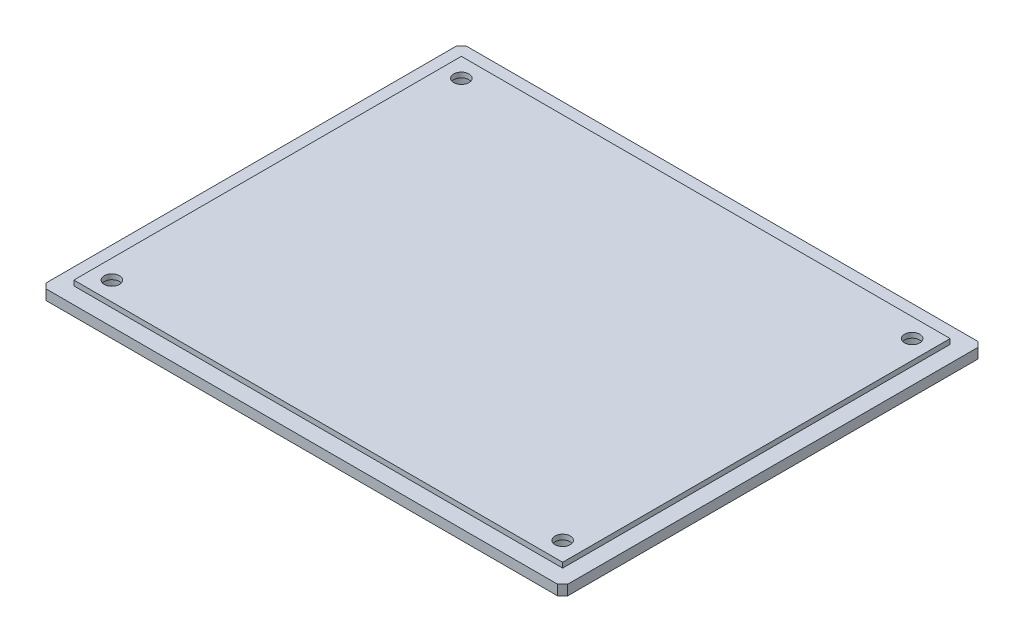
SolidWorks part; units mm, degrees
ref_plane "前视基准面" through (0, 0, 0) normal (0, 0, 1) x (1, 0, 0)
ref_plane "上视基准面" through (0, 0, 0) normal (0, 1, 0) x (1, 0, 0)
ref_plane "右视基准面" through (0, 0, 0) normal (1, 0, 0) x (0, 0, -1)
other "Configuration Table"
sketch "Sketch1" plane through (0, 0, 0) normal (0, 1, 0) x (1, 0, 0)
  line L1 (-51.5, 41.5) -> (51.5, 41.5)
  line L2 (-51.5, 41.5) -> (-51.5, -41.5)
  line L3 (-51.5, -41.5) -> (51.5, -41.5)
  line L4 (51.5, 41.5) -> (51.5, -41.5)
  line L5 (-51.5, 41.5) -> (51.5, -41.5) construction
  line L6 (-51.5, -41.5) -> (51.5, 41.5) construction
  point P0 (0, 0)
  dimension "D1" = 103
  dimension "D2" = 83
extrude "Boss-Extrude1" add sketch "Sketch1" along normal blind 2
sketch "Sketch2" plane through (0, 2, 0) normal (0, 1, 0) x (1, 0, 0)
  line L1 (-48.25, 38.25) -> (48.25, 38.25)
  line L2 (-48.25, 38.25) -> (-48.25, -38.25)
  line L3 (-48.25, -38.25) -> (48.25, -38.25)
  line L4 (48.25, 38.25) -> (48.25, -38.25)
  line L5 (-48.25, 38.25) -> (48.25, -38.25) construction
  line L6 (-48.25, -38.25) -> (48.25, 38.25) construction
  point P0 (0, 0)
  dimension "D1" = 96.5
  dimension "D2" = 76.5
extrude "Boss-Extrude2" add sketch "Sketch2" along normal blind 1
chamfer "Chamfer1" distance 1 angle 45 4 edges at (51.5, 1, -41.5) (51.5, 1, 41.5) (-51.5, 1, 41.5) (-51.5, 1, -41.5)
sketch "Sketch3" plane through (0, 3, 0) normal (0, 1, 0) x (1, 0, 0)
  line L1 (-44.5, 34.5) -> (44.5, 34.5)
  line L2 (-44.5, 34.5) -> (-44.5, -34.5)
  line L3 (-44.5, -34.5) -> (44.5, -34.5)
  line L4 (44.5, 34.5) -> (44.5, -34.5)
  line L5 (-44.5, 34.5) -> (44.5, -34.5) construction
  line L6 (-44.5, -34.5) -> (44.5, 34.5) construction
  circle A0 centre (-44.5, 34.5) radius 1.5
  circle A1 centre (44.5, 34.5) radius 1.5
  circle A2 centre (44.5, -34.5) radius 1.5
  circle A3 centre (-44.5, -34.5) radius 1.5
  point P0 (0, 0)
  dimension "D3" = 3
  dimension "D1" = 89
  dimension "D2" = 69
  dimension "D4" = 2
  dimension "D5" = 2
extrude "Cut-Extrude1" cut sketch "Sketch3" against normal through all contours A0 | A1 | A3 | A2
sketch "Sketch5" plane through (0, 0, 0) normal (0, -1, 0) x (1, 0, 0)
  circle A0 centre (-44.5, 34.5) radius 2.8
  circle A1 centre (44.5, 34.5) radius 2.8
  circle A2 centre (44.5, -34.5) radius 2.8
  circle A3 centre (-44.5, -34.5) radius 2.8
  dimension "D1" = 5.6
  dimension "D2" = 2
  dimension "D3" = 2
extrude "Cut-Extrude2" cut sketch "Sketch5" against normal blind 2
